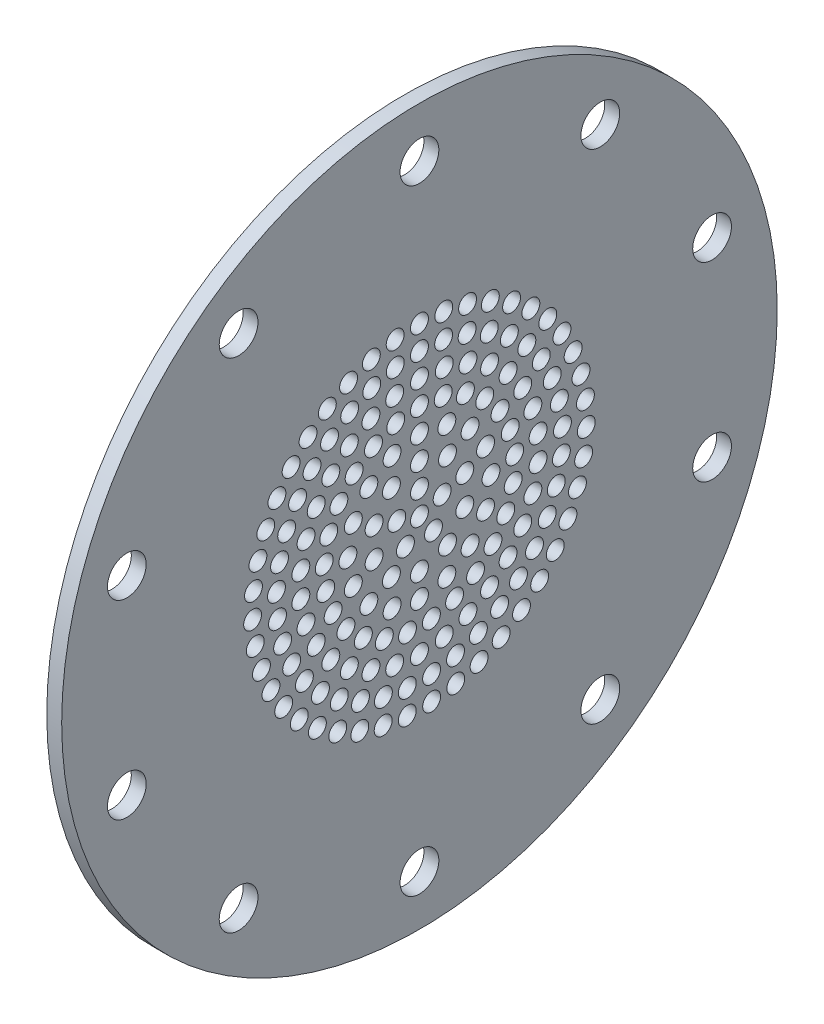
SolidWorks part; units mm, degrees
material "AISI 316 Stainless Steel Sheet (SS)"
ref_plane "Front Plane" through (0, 0, 0) normal (0, 0, 1) x (1, 0, 0)
ref_plane "Top Plane" through (0, 0, 0) normal (0, 1, 0) x (1, 0, 0)
ref_plane "Right Plane" through (0, 0, 0) normal (1, 0, 0) x (0, 0, -1)
sketch "Sketch2" plane through (0, 0, 0) normal (0, 0, 1) x (1, 0, 0)
  line L0 (2.5, 0) -> (2.5, 31)
  line L1 (0, 0) -> (2.5, 0)
  line L2 (0, 0) -> (0, 60)
  line L3 (0, 60) -> (2.5, 60)
  line L4 (2.5, 31) -> (2.5, 60)
  dimension "thickness" = 2.5
  dimension "catbed_radius" = 31
  dimension "step" = 29
revolve "Revolve1" add sketch "Sketch2" angle 360 about L1
sketch "Sketch3" plane through (0, 0, 0) normal (-1, 0, 0) x (0, 0, 1)
  line L0 (0, 0) -> (0, 20) construction
  line L1 (0, 0) -> (4.9738, 19.3717) construction
  line L2 (0, 0) -> (9.6351, 17.5261) construction
  line L3 (0, 0) -> (13.6909, 14.5794) construction
  line L4 (0, 0) -> (16.8866, 10.7165) construction
  line L5 (0, 0) -> (19.0211, 6.1803) construction
  line L6 (0, 0) -> (19.9605, 1.2558) construction
  line L7 (0, 0) -> (19.6457, -3.7476) construction
  line L9 (0, 0) -> (15.4103, -12.7485) construction
  line L10 (0, 0) -> (11.7557, -16.1803) construction
  line L12 (0, 0) -> (2.5067, -19.8423) construction
  line L13 (0, 0) -> (-2.5067, -19.8423) construction
  line L14 (0, 0) -> (-7.3625, -18.5955) construction
  line L15 (0, 0) -> (-11.7557, -16.1803) construction
  line L16 (0, 0) -> (-15.4103, -12.7485) construction
  line L17 (0, 0) -> (-18.0965, -8.5156) construction
  line L18 (0, 0) -> (-19.6457, -3.7476) construction
  line L19 (0, 0) -> (-19.9605, 1.2558) construction
  line L20 (0, 0) -> (-19.0211, 6.1803) construction
  line L21 (0, 0) -> (-16.8866, 10.7165) construction
  line L22 (0, 0) -> (-13.6909, 14.5794) construction
  line L23 (0, 0) -> (-9.6351, 17.5261) construction
  line L24 (0, 0) -> (-4.9738, 19.3717) construction
  line L25 (0, 20) -> (0, 24) construction
  line L26 (0, 24) -> (0, 28) construction
  line L27 (0, 0) -> (18.0965, -8.5156) construction
  line L28 (0, 0) -> (7.3625, -18.5955) construction
  circle A0 centre (4.5922, 11.0866) radius 1.5
  circle A1 centre (0, 0) radius 1.5
  circle A2 centre (0, 4) radius 1.5
  circle A3 centre (0, 8) radius 1.5
  circle A4 centre (0, 12) radius 1.5
  circle A5 centre (0, 16) radius 1.5
  circle A6 centre (0, 20) radius 1.5
  circle A7 centre (3.979, 15.4973) radius 1.5
  circle A8 centre (4.1582, 19.563) radius 1.5
  circle A9 centre (8.4853, 8.4853) radius 1.5
  circle A10 centre (7.7081, 14.0209) radius 1.5
  circle A11 centre (8.1347, 18.2709) radius 1.5
  circle A12 centre (11.0866, 4.5922) radius 1.5
  circle A13 centre (10.9528, 11.6635) radius 1.5
  circle A14 centre (11.7557, 16.1803) radius 1.5
  circle A15 centre (12, 0) radius 1.5
  circle A16 centre (13.5092, 8.5732) radius 1.5
  circle A17 centre (14.8629, 13.3826) radius 1.5
  circle A18 centre (11.0866, -4.5922) radius 1.5
  circle A19 centre (15.2169, 4.9443) radius 1.5
  circle A20 centre (17.3205, 10) radius 1.5
  circle A21 centre (8.4853, -8.4853) radius 1.5
  circle A22 centre (15.9684, 1.0046) radius 1.5
  circle A23 centre (19.0211, 6.1803) radius 1.5
  circle A24 centre (4.5922, -11.0866) radius 1.5
  circle A25 centre (15.7166, -2.9981) radius 1.5
  circle A26 centre (19.8904, 2.0906) radius 1.5
  circle A27 centre (0, -12) radius 1.5
  circle A28 centre (14.4772, -6.8125) radius 1.5
  circle A29 centre (19.8904, -2.0906) radius 1.5
  circle A30 centre (-4.5922, -11.0866) radius 1.5
  circle A31 centre (12.3282, -10.1988) radius 1.5
  circle A32 centre (19.0211, -6.1803) radius 1.5
  circle A33 centre (-8.4853, -8.4853) radius 1.5
  circle A34 centre (9.4046, -12.9443) radius 1.5
  circle A35 centre (17.3205, -10) radius 1.5
  circle A36 centre (-11.0866, -4.5922) radius 1.5
  circle A37 centre (5.89, -14.8764) radius 1.5
  circle A38 centre (14.8629, -13.3826) radius 1.5
  circle A39 centre (-12, 0) radius 1.5
  circle A40 centre (2.0053, -15.8738) radius 1.5
  circle A41 centre (11.7557, -16.1803) radius 1.5
  circle A42 centre (-11.0866, 4.5922) radius 1.5
  circle A43 centre (-2.0053, -15.8738) radius 1.5
  circle A44 centre (8.1347, -18.2709) radius 1.5
  circle A45 centre (-8.4853, 8.4853) radius 1.5
  circle A46 centre (-5.89, -14.8764) radius 1.5
  circle A47 centre (4.1582, -19.563) radius 1.5
  circle A48 centre (-4.5922, 11.0866) radius 1.5
  circle A49 centre (-9.4046, -12.9443) radius 1.5
  circle A50 centre (0, -20) radius 1.5
  circle A51 centre (4.7023, 6.4721) radius 1.5
  circle A52 centre (7.6085, 2.4721) radius 1.5
  circle A53 centre (7.6085, -2.4721) radius 1.5
  circle A54 centre (4.7023, -6.4721) radius 1.5
  circle A55 centre (0, -8) radius 1.5
  circle A56 centre (-4.7023, -6.4721) radius 1.5
  circle A57 centre (-7.6085, -2.4721) radius 1.5
  circle A58 centre (-7.6085, 2.4721) radius 1.5
  circle A59 centre (-4.7023, 6.4721) radius 1.5
  circle A60 centre (3.8042, 1.2361) radius 1.5
  circle A61 centre (2.3511, -3.2361) radius 1.5
  circle A62 centre (-2.3511, -3.2361) radius 1.5
  circle A63 centre (-3.8042, 1.2361) radius 1.5
  circle A64 centre (-12.3282, -10.1988) radius 1.5
  circle A65 centre (-4.1582, -19.563) radius 1.5
  circle A66 centre (-14.4772, -6.8125) radius 1.5
  circle A67 centre (-8.1347, -18.2709) radius 1.5
  circle A68 centre (-15.7166, -2.9981) radius 1.5
  circle A69 centre (-11.7557, -16.1803) radius 1.5
  circle A70 centre (-5.4723, -15.0351) radius 1.5 [skipped]
  circle A71 centre (-6.8404, -18.7939) radius 1.5 [skipped]
  circle A72 centre (-4.1042, -11.2763) radius 1.5 [skipped]
  circle A73 centre (-10.2846, -12.2567) radius 1.5 [skipped]
  circle A74 centre (-12.8558, -15.3209) radius 1.5 [skipped]
  circle A75 centre (-7.7135, -9.1925) radius 1.5 [skipped]
  circle A76 centre (-13.8564, -8) radius 1.5 [skipped]
  circle A77 centre (-17.3205, -10) radius 1.5 [skipped]
  circle A78 centre (-10.3923, -6) radius 1.5 [skipped]
  circle A79 centre (-15.7569, -2.7784) radius 1.5 [skipped]
  circle A80 centre (-19.6962, -3.473) radius 1.5 [skipped]
  circle A81 centre (-11.8177, -2.0838) radius 1.5 [skipped]
  circle A82 centre (-15.7569, 2.7784) radius 1.5 [skipped]
  circle A83 centre (-19.6962, 3.473) radius 1.5 [skipped]
  circle A84 centre (-11.8177, 2.0838) radius 1.5 [skipped]
  circle A85 centre (-13.8564, 8) radius 1.5 [skipped]
  circle A86 centre (-17.3205, 10) radius 1.5 [skipped]
  circle A87 centre (-10.3923, 6) radius 1.5 [skipped]
  circle A88 centre (-10.2846, 12.2567) radius 1.5 [skipped]
  circle A89 centre (-12.8558, 15.3209) radius 1.5 [skipped]
  circle A90 centre (-7.7135, 9.1925) radius 1.5 [skipped]
  circle A91 centre (-5.4723, 15.0351) radius 1.5 [skipped]
  circle A92 centre (-6.8404, 18.7939) radius 1.5 [skipped]
  circle A93 centre (-4.1042, 11.2763) radius 1.5 [skipped]
  circle A94 centre (-15.9684, 1.0046) radius 1.5
  circle A95 centre (-14.8629, -13.3826) radius 1.5
  circle A96 centre (-15.2169, 4.9443) radius 1.5
  circle A97 centre (-17.3205, -10) radius 1.5
  circle A98 centre (-13.5092, 8.5732) radius 1.5
  circle A99 centre (-19.0211, -6.1803) radius 1.5
  circle A100 centre (6.8404, 18.7939) radius 1.5 [skipped]
  circle A101 centre (10.2846, 12.2567) radius 1.5 [skipped]
  circle A102 centre (12.8558, 15.3209) radius 1.5 [skipped]
  circle A103 centre (7.7135, 9.1925) radius 1.5 [skipped]
  circle A104 centre (13.8564, 8) radius 1.5 [skipped]
  circle A105 centre (17.3205, 10) radius 1.5 [skipped]
  circle A106 centre (10.3923, 6) radius 1.5 [skipped]
  circle A107 centre (15.7569, 2.7784) radius 1.5 [skipped]
  circle A108 centre (11.8177, 2.0838) radius 1.5 [skipped]
  circle A109 centre (15.7569, -2.7784) radius 1.5 [skipped]
  circle A110 centre (11.8177, -2.0838) radius 1.5 [skipped]
  circle A111 centre (13.8564, -8) radius 1.5 [skipped]
  circle A112 centre (17.3205, -10) radius 1.5 [skipped]
  circle A113 centre (10.3923, -6) radius 1.5 [skipped]
  circle A114 centre (10.2846, -12.2567) radius 1.5 [skipped]
  circle A115 centre (12.8558, -15.3209) radius 1.5 [skipped]
  circle A116 centre (7.7135, -9.1925) radius 1.5 [skipped]
  circle A117 centre (-10.9528, 11.6635) radius 1.5
  circle A118 centre (-19.8904, -2.0906) radius 1.5
  circle A119 centre (5.4723, 15.0351) radius 1.5 [skipped]
  circle A120 centre (4.1042, 11.2763) radius 1.5 [skipped]
  circle A121 centre (-7.7081, 14.0209) radius 1.5
  circle A122 centre (-19.8904, 2.0906) radius 1.5
  circle A123 centre (4.1042, -11.2763) radius 1.5 [skipped]
  circle A124 centre (0, -12) radius 1.5 [skipped]
  circle A125 centre (5.4723, -15.0351) radius 1.5 [skipped]
  circle A126 centre (0, -16) radius 1.5 [skipped]
  circle A127 centre (0, -20) radius 1.5 [skipped]
  circle A128 centre (6.8404, -18.7939) radius 1.5 [skipped]
  circle A129 centre (19.6962, -3.473) radius 1.5 [skipped]
  circle A130 centre (19.6962, 3.473) radius 1.5 [skipped]
  circle A131 centre (18.4776, 7.6537) radius 1.5 [skipped]
  circle A132 centre (16, 0) radius 1.5 [skipped]
  circle A133 centre (20, 0) radius 1.5 [skipped]
  circle A134 centre (18.4776, -7.6537) radius 1.5 [skipped]
  circle A135 centre (14.7821, 6.1229) radius 1.5 [skipped]
  circle A136 centre (11.3137, -11.3137) radius 1.5 [skipped]
  circle A137 centre (14.1421, -14.1421) radius 1.5 [skipped]
  circle A138 centre (6.1229, -14.7821) radius 1.5 [skipped]
  circle A139 centre (7.6537, -18.4776) radius 1.5 [skipped]
  circle A140 centre (0, -16) radius 1.5 [skipped]
  circle A141 centre (0, -20) radius 1.5 [skipped]
  circle A142 centre (-6.1229, -14.7821) radius 1.5 [skipped]
  circle A143 centre (-7.6537, -18.4776) radius 1.5 [skipped]
  circle A144 centre (-11.3137, -11.3137) radius 1.5 [skipped]
  circle A145 centre (-14.1421, -14.1421) radius 1.5 [skipped]
  circle A146 centre (-20, 0) radius 1.5 [skipped]
  circle A147 centre (-14.7821, -6.1229) radius 1.5 [skipped]
  circle A148 centre (-18.4776, -7.6537) radius 1.5 [skipped]
  circle A149 centre (-16, 0) radius 1.5 [skipped]
  circle A150 centre (-14.1421, 14.1421) radius 1.5 [skipped]
  circle A151 centre (-11.3137, 11.3137) radius 1.5 [skipped]
  circle A152 centre (-18.4776, 7.6537) radius 1.5 [skipped]
  circle A153 centre (-14.7821, 6.1229) radius 1.5 [skipped]
  circle A154 centre (-6.1229, 14.7821) radius 1.5 [skipped]
  circle A155 centre (-7.6537, 18.4776) radius 1.5 [skipped]
  circle A156 centre (14.1421, 14.1421) radius 1.5 [skipped]
  circle A157 centre (11.3137, 11.3137) radius 1.5 [skipped]
  circle A158 centre (6.1229, 14.7821) radius 1.5 [skipped]
  circle A159 centre (7.6537, 18.4776) radius 1.5 [skipped]
  circle A160 centre (14.7821, -6.1229) radius 1.5 [skipped]
  circle A161 centre (-3.979, 15.4973) radius 1.5
  circle A162 centre (-19.0211, 6.1803) radius 1.5
  circle A163 centre (0, 0) radius 31 construction
  circle A164 centre (0, 24) radius 1.5
  circle A165 centre (0, 28) radius 1.5
  circle A166 centre (16.8866, 10.7165) radius 1.5 [skipped]
  circle A167 centre (13.6909, 14.5794) radius 1.5 [skipped]
  circle A168 centre (4.9738, 19.3717) radius 1.5 [skipped]
  circle A169 centre (9.6351, 17.5261) radius 1.5 [skipped]
  circle A170 centre (19.0211, 6.1803) radius 1.5 [skipped]
  circle A171 centre (19.9605, 1.2558) radius 1.5 [skipped]
  circle A172 centre (19.6457, -3.7476) radius 1.5 [skipped]
  circle A173 centre (18.0965, -8.5156) radius 1.5 [skipped]
  circle A174 centre (15.4103, -12.7485) radius 1.5 [skipped]
  circle A175 centre (11.7557, -16.1803) radius 1.5 [skipped]
  circle A176 centre (7.3625, -18.5955) radius 1.5 [skipped]
  circle A177 centre (-7.3625, -18.5955) radius 1.5 [skipped]
  circle A178 centre (2.5067, -19.8423) radius 1.5 [skipped]
  circle A179 centre (-2.5067, -19.8423) radius 1.5 [skipped]
  circle A180 centre (-15.4103, -12.7485) radius 1.5 [skipped]
  circle A181 centre (-11.7557, -16.1803) radius 1.5 [skipped]
  circle A182 centre (-19.6457, -3.7476) radius 1.5 [skipped]
  circle A183 centre (-18.0965, -8.5156) radius 1.5 [skipped]
  circle A184 centre (-19.9605, 1.2558) radius 1.5 [skipped]
  circle A185 centre (-19.0211, 6.1803) radius 1.5 [skipped]
  circle A186 centre (-13.6909, 14.5794) radius 1.5 [skipped]
  circle A187 centre (-16.8866, 10.7165) radius 1.5 [skipped]
  circle A188 centre (-9.6351, 17.5261) radius 1.5 [skipped]
  circle A189 centre (-4.9738, 19.3717) radius 1.5 [skipped]
  circle A190 centre (-17.3205, 10) radius 1.5
  circle A191 centre (-14.8629, 13.3826) radius 1.5
  circle A192 centre (-11.7557, 16.1803) radius 1.5
  circle A193 centre (-8.1347, 18.2709) radius 1.5
  circle A194 centre (-4.1582, 19.563) radius 1.5
  circle A195 centre (4.056, 23.6548) radius 1.5
  circle A196 centre (7.9954, 22.6291) radius 1.5
  circle A197 centre (11.7047, 20.9523) radius 1.5
  circle A198 centre (15.0773, 18.6729) radius 1.5
  circle A199 centre (18.0161, 15.8562) radius 1.5
  circle A200 centre (20.4367, 12.5834) radius 1.5
  circle A201 centre (22.2693, 8.9486) radius 1.5
  circle A202 centre (23.4613, 5.0563) radius 1.5
  circle A203 centre (23.9784, 1.0186) radius 1.5
  circle A204 centre (23.8056, -3.0484) radius 1.5
  circle A205 centre (22.948, -7.0277) radius 1.5
  circle A206 centre (21.4302, -10.8049) radius 1.5
  circle A207 centre (19.2959, -14.2712) radius 1.5
  circle A208 centre (16.6065, -17.3269) radius 1.5
  circle A209 centre (13.4394, -19.8842) radius 1.5
  circle A210 centre (9.8856, -21.8695) radius 1.5
  circle A211 centre (6.0475, -23.2256) radius 1.5
  circle A212 centre (2.0353, -23.9135) radius 1.5
  circle A213 centre (-2.0353, -23.9135) radius 1.5
  circle A214 centre (-6.0475, -23.2256) radius 1.5
  circle A215 centre (-9.8856, -21.8695) radius 1.5
  circle A216 centre (-13.4394, -19.8842) radius 1.5
  circle A217 centre (-16.6065, -17.3269) radius 1.5
  circle A218 centre (-19.2959, -14.2712) radius 1.5
  circle A219 centre (-21.4302, -10.8049) radius 1.5
  circle A220 centre (-22.948, -7.0277) radius 1.5
  circle A221 centre (-23.8056, -3.0484) radius 1.5
  circle A222 centre (-23.9784, 1.0186) radius 1.5
  circle A223 centre (-23.4613, 5.0563) radius 1.5
  circle A224 centre (-22.2693, 8.9486) radius 1.5
  circle A225 centre (-20.4367, 12.5834) radius 1.5
  circle A226 centre (-18.0161, 15.8562) radius 1.5
  circle A227 centre (-15.0773, 18.6729) radius 1.5
  circle A228 centre (-11.7047, 20.9523) radius 1.5
  circle A229 centre (-7.9954, 22.6291) radius 1.5
  circle A230 centre (-4.056, 23.6548) radius 1.5
  circle A231 centre (4.0768, 27.7016) radius 1.5
  circle A232 centre (8.0668, 26.8128) radius 1.5
  circle A233 centre (11.8848, 25.3526) radius 1.5
  circle A234 centre (15.4495, 23.3519) radius 1.5
  circle A235 centre (18.6849, 20.8536) radius 1.5
  circle A236 centre (21.5221, 17.9108) radius 1.5
  circle A237 centre (23.9006, 14.5863) radius 1.5
  circle A238 centre (25.7697, 10.9509) radius 1.5
  circle A239 centre (27.0895, 7.0821) radius 1.5
  circle A240 centre (27.832, 3.0624) radius 1.5
  circle A241 centre (27.9813, -1.0226) radius 1.5
  circle A242 centre (27.5342, -5.0858) radius 1.5
  circle A243 centre (26.5003, -9.0407) radius 1.5
  circle A244 centre (24.9016, -12.8028) radius 1.5
  circle A245 centre (22.7721, -16.292) radius 1.5
  circle A246 centre (20.1573, -19.4341) radius 1.5
  circle A247 centre (17.1129, -22.1619) radius 1.5
  circle A248 centre (13.7037, -24.4174) radius 1.5
  circle A249 centre (10.0025, -26.1525) radius 1.5
  circle A250 centre (6.088, -27.3301) radius 1.5
  circle A251 centre (2.0439, -27.9253) radius 1.5
  circle A252 centre (-2.0439, -27.9253) radius 1.5
  circle A253 centre (-6.088, -27.3301) radius 1.5
  circle A254 centre (-10.0025, -26.1525) radius 1.5
  circle A255 centre (-13.7037, -24.4174) radius 1.5
  circle A256 centre (-17.1129, -22.1619) radius 1.5
  circle A257 centre (-20.1573, -19.4341) radius 1.5
  circle A258 centre (-22.7721, -16.292) radius 1.5
  circle A259 centre (-24.9016, -12.8028) radius 1.5
  circle A260 centre (-26.5003, -9.0407) radius 1.5
  circle A261 centre (-27.5342, -5.0858) radius 1.5
  circle A262 centre (-27.9813, -1.0226) radius 1.5
  circle A263 centre (-27.832, 3.0624) radius 1.5
  circle A264 centre (-27.0895, 7.0821) radius 1.5
  circle A265 centre (-25.7697, 10.9509) radius 1.5
  circle A266 centre (-23.9006, 14.5863) radius 1.5
  circle A267 centre (-21.5221, 17.9108) radius 1.5
  circle A268 centre (-18.6849, 20.8536) radius 1.5
  circle A269 centre (-15.4495, 23.3519) radius 1.5
  circle A270 centre (-11.8848, 25.3526) radius 1.5
  circle A271 centre (-8.0668, 26.8128) radius 1.5
  circle A272 centre (-4.0768, 27.7016) radius 1.5
  point P1 (6.1229, 14.7821)
  point P4 (0, 4)
  point P6 (0, 8)
  point P7 (0, 12)
  point P8 (0, 16)
  point P18 (5.4723, -15.0351)
  point P19 (10.2846, -12.2567)
  point P20 (7.7135, -9.1925)
  point P21 (4.1042, 11.2763)
  point P22 (-5.4723, 15.0351)
  point P23 (13.8564, -8)
  point P24 (10.3923, -6)
  point P25 (15.7569, -2.7784)
  point P26 (11.8177, -2.0838)
  point P27 (15.7569, 2.7784)
  point P28 (11.8177, 2.0838)
  point P29 (5.4723, 15.0351)
  point P30 (7.7135, 9.1925)
  point P31 (13.8564, 8)
  point P32 (10.3923, 6)
  point P33 (10.2846, 12.2567)
  point P34 (-4.1042, 11.2763)
  point P35 (-10.2846, 12.2567)
  point P36 (-7.7135, 9.1925)
  point P37 (-13.8564, 8)
  point P38 (-10.3923, 6)
  point P39 (-15.7569, 2.7784)
  point P40 (-11.8177, 2.0838)
  point P41 (-15.7569, -2.7784)
  point P42 (-11.8177, -2.0838)
  point P43 (-13.8564, -8)
  point P44 (-10.3923, -6)
  point P45 (-10.2846, -12.2567)
  point P46 (-7.7135, -9.1925)
  point P47 (-5.4723, -15.0351)
  point P48 (-4.1042, -11.2763)
  point P49 (-11.3137, 11.3137)
  point P50 (-16, 0)
  point P51 (-6.1229, -14.7821)
  point P52 (4.5922, 11.0866)
  point P53 (0, -16)
  point P56 (6.1229, -14.7821)
  point P57 (0, -16)
  point P58 (11.3137, -11.3137)
  point P59 (14.7821, -6.1229)
  point P60 (8.4853, 8.4853)
  point P61 (11.3137, 11.3137)
  point P64 (16, 0)
  point P65 (14.7821, 6.1229)
  point P68 (11.0866, 4.5922)
  point P72 (3.979, 15.4973)
  point P76 (12, 0)
  point P77 (4.1042, -11.2763)
  point P81 (7.7081, 14.0209)
  point P85 (0, -12)
  point P87 (11.0866, -4.5922)
  point P88 (10.9528, 11.6635)
  point P95 (8.4853, -8.4853)
  point P96 (13.5092, 8.5732)
  point P103 (4.5922, -11.0866)
  point P104 (15.2169, 4.9443)
  point P111 (0, -12)
  point P112 (15.9684, 1.0046)
  point P119 (-4.5922, -11.0866)
  point P120 (15.7166, -2.9981)
  point P127 (-8.4853, -8.4853)
  point P128 (-11.3137, -11.3137)
  point P131 (14.4772, -6.8125)
  point P135 (-11.0866, -4.5922)
  point P136 (-14.7821, -6.1229)
  point P140 (12.3282, -10.1988)
  point P143 (-12, 0)
  point P148 (9.4046, -12.9443)
  point P151 (-11.0866, 4.5922)
  point P152 (-14.7821, 6.1229)
  point P156 (0, 0)
  point P158 (5.89, -14.8764)
  point P160 (-8.4853, 8.4853)
  point P166 (2.0053, -15.8738)
  point P168 (-4.5922, 11.0866)
  point P169 (-6.1229, 14.7821)
  point P174 (0, 0)
  point P176 (0, 0)
  point P183 (0, 0)
  point P278 (0, 0)
  point P307 (0, 0)
  point P368 (-2.0053, -15.8738)
  point P373 (-5.89, -14.8764)
  point P378 (-9.4046, -12.9443)
  point P383 (-12.3282, -10.1988)
  point P388 (-14.4772, -6.8125)
  point P393 (-15.7166, -2.9981)
  point P398 (-15.9684, 1.0046)
  point P403 (-15.2169, 4.9443)
  point P408 (-13.5092, 8.5732)
  point P413 (-10.9528, 11.6635)
  point P418 (-7.7081, 14.0209)
  point P423 (-3.979, 15.4973)
  point P427 (0, 0)
  point P516 (0, 0)
  point P588 (0, 0)
  point P673 (0, 0)
  dimension "D3" = 3
  dimension "D13" = 62
  dimension "D15" = 3
  dimension "D16" = 3
  dimension "D1" = 4
  dimension "D2" = 4
  dimension "D4" = 4
  dimension "D5" = 4
  dimension "D6" = 4
  dimension "D12" = 4
  dimension "D14" = 4
  dimension "D8" = 18
  dimension "D7" = 16
  dimension "D9" = 10
  dimension "D10" = 5
  dimension "D11" = 25
  dimension "D17" = 30
  dimension "D18" = 37
  dimension "D19" = 43
extrude "Cut-Extrude6" cut sketch "Sketch3" against normal blind 10
sketch "Sketch4" plane through (0, 0, 0) normal (-1, 0, 0) x (0, 0, 1)
  line L0 (0, 0) -> (0, 51.6) construction
  circle A0 centre (0, 51.6) radius 3.25
  circle A1 centre (30.3297, 41.7453) radius 3.25
  circle A2 centre (49.0745, 15.9453) radius 3.25
  circle A3 centre (49.0745, -15.9453) radius 3.25
  circle A4 centre (30.3297, -41.7453) radius 3.25
  circle A5 centre (0, -51.6) radius 3.25
  circle A6 centre (-30.3297, -41.7453) radius 3.25
  circle A7 centre (-49.0745, -15.9453) radius 3.25
  circle A8 centre (-49.0745, 15.9453) radius 3.25
  circle A9 centre (-30.3297, 41.7453) radius 3.25
  point P25 (0, 0)
  dimension "D2" = 6.5
  dimension "D1" = 51.6
  dimension "D3" = 10
extrude "Cut-Extrude7" cut sketch "Sketch4" against normal blind 10
equation "\"D5@Sketch3\"=\"D2@Sketch3\""
equation "\"D4@Sketch3\"=\"D2@Sketch3\""
equation "\"D6@Sketch3\"=\"D4@Sketch3\""
equation "\"D1@Sketch3\"=\"D6@Sketch3\""
equation "\"D12@Sketch3\"=\"D4@Sketch3\""
equation "\"D14@Sketch3\"=\"D5@Sketch3\""
